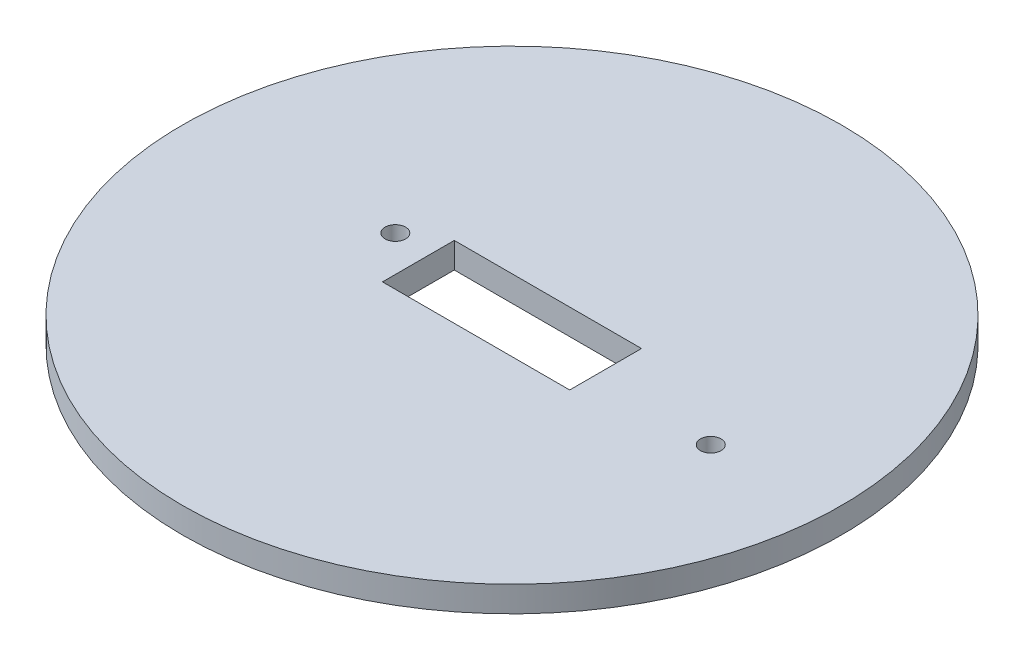
SolidWorks part; units mm, degrees
ref_plane "Front Plane" through (0, 0, 0) normal (0, 0, 1) x (1, 0, 0)
ref_plane "Top Plane" through (0, 0, 0) normal (0, 1, 0) x (1, 0, 0)
ref_plane "Right Plane" through (0, 0, 0) normal (1, 0, 0) x (0, 0, -1)
sketch "Sketch2" plane through (0, 0, 0) normal (0, 1, 0) x (1, 0, 0)
  circle A0 centre (0, 0) radius 25.7
extrude "Boss-Extrude1" add sketch "Sketch2" along normal blind 2
sketch "Sketch3" plane through (0, 2, 0) normal (0, 1, 0) x (1, 0, 0)
  line L1 (-7.3, -2.8) -> (7.3, -2.8)
  line L2 (-7.3, -2.8) -> (-7.3, 2.8)
  line L3 (-7.3, 2.8) -> (7.3, 2.8)
  line L4 (7.3, -2.8) -> (7.3, 2.8)
  line L5 (-7.3, -2.8) -> (7.3, 2.8) construction
  line L6 (-7.3, 2.8) -> (7.3, -2.8) construction
  point P0 (0, 0)
  point P6 (0, 0)
extrude "Cut-Extrude1" cut sketch "Sketch3" against normal through all
hole_wizard "Ø1.6 (1.6) Diameter Hole1" positions "3DSketch2" profile "Sketch5" hole size "Ø1.6" standard "ANSI Metric" end condition through all
sketch3d "3DSketch2"
  point P0 (-10.1, 2, -1)
  point P3 (16.5, 2, 1)
sketch "Sketch5" plane through (-10.1, 2, -1) normal (1, 0, 0) x (0, 0, 1)
  line L0 (0, 0) -> (0, 2)
  line L1 (0, 2) -> (0.8, 2)
  line L2 (0.8, 2) -> (0.8, 0)
  line L5 (0.8, 0) -> (0, 0)
  line L11 (0, -6.35) -> (0, 107.95) construction
  dimension "Thru Hole Dia." = 1.6
  dimension "Thru Hole Depth" = 2
